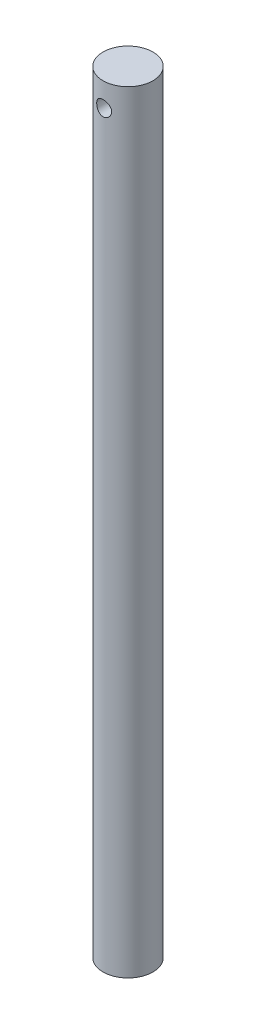
SolidWorks part; units mm, degrees
ref_plane "前视基准面" through (0, 0, 0) normal (0, 0, 1) x (1, 0, 0)
ref_plane "上视基准面" through (0, 0, 0) normal (0, 1, 0) x (1, 0, 0)
ref_plane "右视基准面" through (0, 0, 0) normal (1, 0, 0) x (0, 0, -1)
other "Configuration Table"
sketch "草图2" plane through (0, 0, 0) normal (0, 1, 0) x (1, 0, 0)
  circle A0 centre (0, 0) radius 10
  dimension "D1" = 20
extrude "凸台-拉伸1" add sketch "草图2" along normal blind 309.5
sketch "草图3" plane through (0, 0, 0) normal (0, 0, 1) x (1, 0, 0)
  line L0 (0, -3.3) -> (0, 3.3) construction
  line L1 (10, 309.5) -> (-10, 309.5) construction
  circle A0 centre (0, 300) radius 3
  dimension "D1" = 6
  dimension "D2" = 9.5
extrude "切除-拉伸2" cut sketch "草图3" against normal through all and the other way through all
